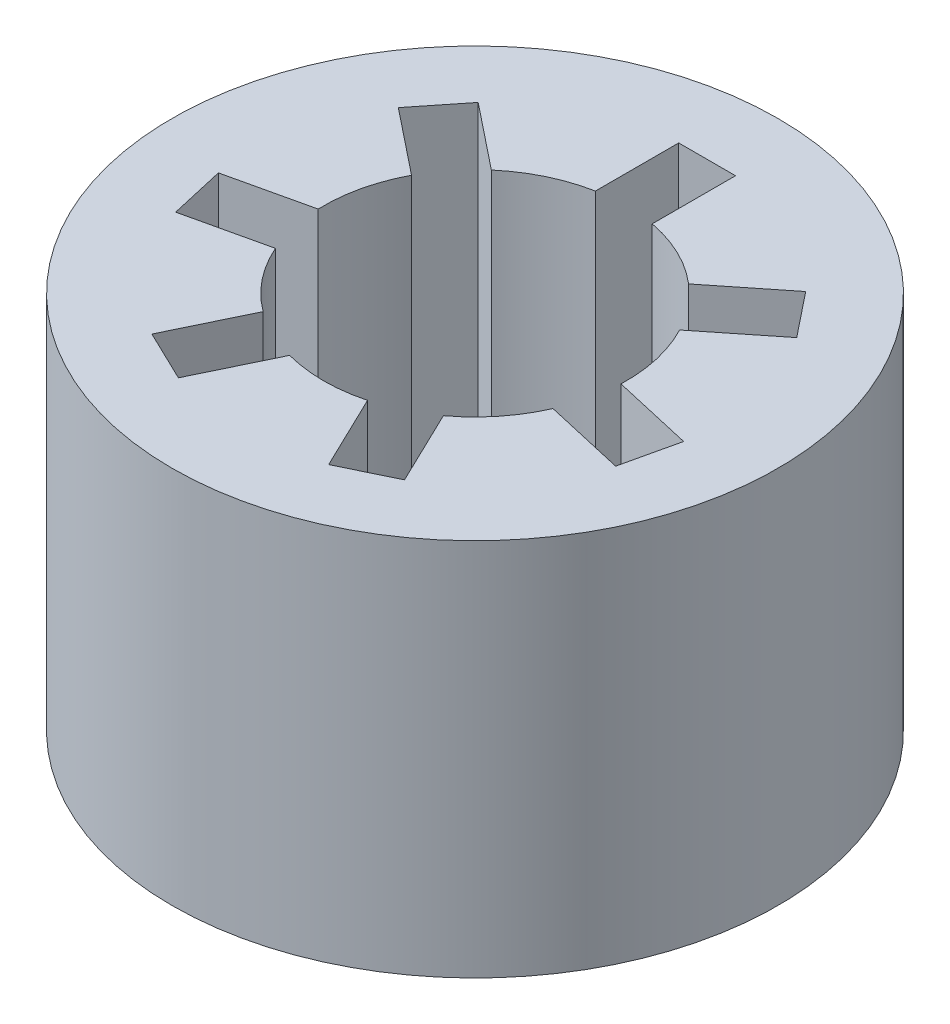
SolidWorks part; units mm, degrees
ref_plane "Front Plane" through (0, 0, 0) normal (0, 0, 1) x (1, 0, 0)
ref_plane "Top Plane" through (0, 0, 0) normal (0, 1, 0) x (1, 0, 0)
ref_plane "Right Plane" through (0, 0, 0) normal (1, 0, 0) x (0, 0, -1)
sketch "Casing" plane through (0, 0, 0) normal (0, 1, 0) x (1, 0, 0)
  circle A0 centre (0, 0) radius 4
  circle A1 centre (0, 0) radius 8
  point P11 (0, 0)
  point P12 (0, 0)
  point P13 (1, 6.373)
  point P14 (0, 0)
  point P15 (0, 0)
  point P16 (0, 0)
  dimension "D1" = 8
  dimension "D2" = 16
sketch "Notch" plane through (0, 0, 0) normal (0, 1, 0) x (1, 0, 0)
  line L0 (0, 0) -> (0, 8) construction
  line L1 (-0.75, 3.9291) -> (0.75, 3.9291)
  line L2 (-0.75, 3.9291) -> (-0.75, 6.1291)
  line L3 (-0.75, 6.1291) -> (0.75, 6.1291)
  line L4 (0.75, 3.9291) -> (0.75, 6.1291)
  line L5 (-2.6042, 3.0361) -> (-4.3243, 4.4078)
  line L6 (-5.2595, 3.235) -> (-4.3243, 4.4078)
  line L7 (-3.5395, 1.8634) -> (-5.2595, 3.235)
  line L8 (-3.5395, 1.8634) -> (-2.6042, 3.0361)
  line L9 (-3.9974, -0.1431) -> (-6.1423, -0.6326)
  line L10 (-5.8085, -2.095) -> (-6.1423, -0.6326)
  line L11 (-3.6637, -1.6055) -> (-5.8085, -2.095)
  line L12 (-3.6637, -1.6055) -> (-3.9974, -0.1431)
  line L13 (-2.3805, -3.2145) -> (-3.335, -5.1967)
  line L14 (-1.9836, -5.8475) -> (-3.335, -5.1967)
  line L15 (-1.029, -3.8654) -> (-1.9836, -5.8475)
  line L16 (-1.029, -3.8654) -> (-2.3805, -3.2145)
  line L17 (1.029, -3.8654) -> (1.9836, -5.8475)
  line L18 (3.335, -5.1967) -> (1.9836, -5.8475)
  line L19 (2.3805, -3.2145) -> (3.335, -5.1967)
  line L20 (2.3805, -3.2145) -> (1.029, -3.8654)
  line L21 (3.6637, -1.6055) -> (5.8085, -2.095)
  line L22 (6.1423, -0.6326) -> (5.8085, -2.095)
  line L23 (3.9974, -0.1431) -> (6.1423, -0.6326)
  line L24 (3.9974, -0.1431) -> (3.6637, -1.6055)
  line L25 (3.5395, 1.8634) -> (5.2595, 3.235)
  line L26 (4.3243, 4.4078) -> (5.2595, 3.235)
  line L27 (2.6042, 3.0361) -> (4.3243, 4.4078)
  line L28 (2.6042, 3.0361) -> (3.5395, 1.8634)
  circle A1 centre (0, 0) radius 8 construction
  circle A2 centre (0, 0) radius 4 construction
  point P38 (0, 0)
  dimension "D1" = 2.2
  dimension "D2" = 1.5
  dimension "D3" = 7
extrude "Boss-Extrude1" add sketch "Casing" along normal blind 10
extrude "Cut-Extrude1" cut sketch "Notch" along normal up to next
